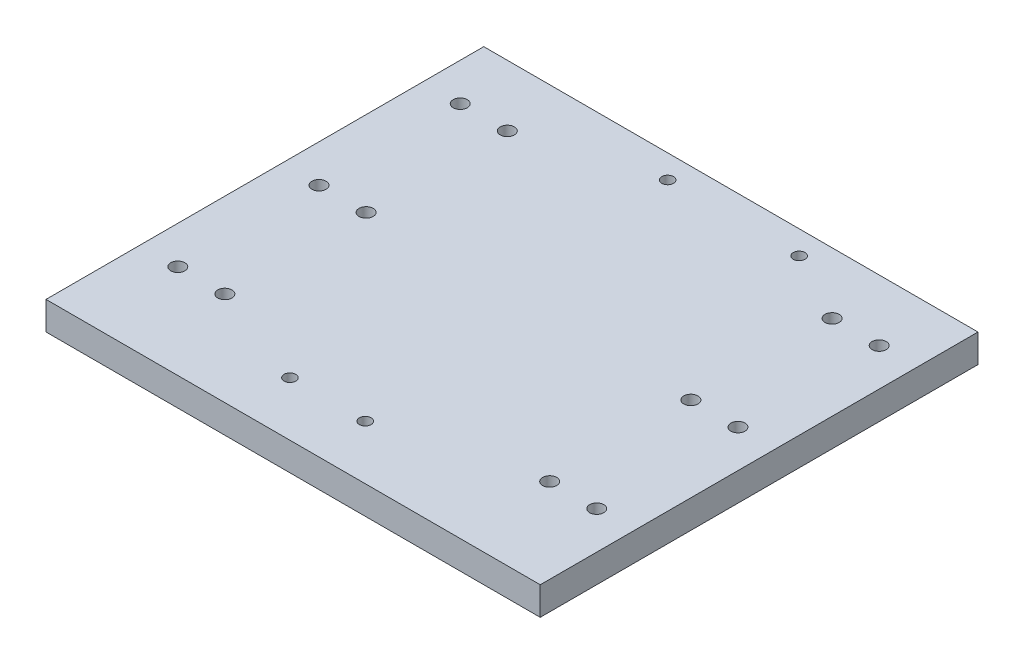
SolidWorks part; units mm, degrees
ref_plane "Plan de face" through (0, 0, 0) normal (0, 0, 1) x (1, 0, 0)
ref_plane "Plan de dessus" through (0, 0, 0) normal (0, 1, 0) x (1, 0, 0)
ref_plane "Plan de droite" through (0, 0, 0) normal (1, 0, 0) x (0, 0, -1)
sketch "Esquisse1" plane through (0, 0, 0) normal (0, 1, 0) x (1, 0, 0)
  line L0 (0, 93) -> (0, 0) construction
  line L1 (-52.5, 93) -> (52.5, 93)
  line L2 (-52.5, 93) -> (-52.5, 0)
  line L3 (-52.5, 0) -> (52.5, 0)
  line L4 (52.5, 93) -> (52.5, 0)
  circle A0 centre (34.5, 80) radius 1.5
  circle A1 centre (44.5, 80) radius 1.5
  circle A2 centre (34.5, 50) radius 1.5
  circle A3 centre (44.5, 50) radius 1.5
  circle A4 centre (34.5, 20) radius 1.5
  circle A5 centre (44.5, 20) radius 1.5
  circle A6 centre (-44.5, 20) radius 1.5
  circle A7 centre (-34.5, 20) radius 1.5
  circle A8 centre (-44.5, 50) radius 1.5
  circle A9 centre (-34.5, 50) radius 1.5
  circle A10 centre (-44.5, 80) radius 1.5
  circle A11 centre (-34.5, 80) radius 1.5
  circle A12 centre (-8.44, 88) radius 1.25
  circle A13 centre (19.5, 88) radius 1.25
  circle A14 centre (-12.18, 11.5) radius 1.25
  circle A15 centre (3.82, 11.5) radius 1.25
  dimension "D3" = 10
  dimension "D4" = 8
  dimension "D5" = 13
  dimension "D6" = 3
  dimension "D9" = 2.5
  dimension "D11" = 33
  dimension "D12" = 5
  dimension "D1" = 93
  dimension "D2" = 105
  dimension "D8" = 30
  dimension "D10" = 27.94
  dimension "D13" = 16
  dimension "D14" = 15.68
  dimension "D15" = 76.5
  dimension "D7" = 3
extrude "Boss.-Extru.1" add sketch "Esquisse1" along normal blind 6
